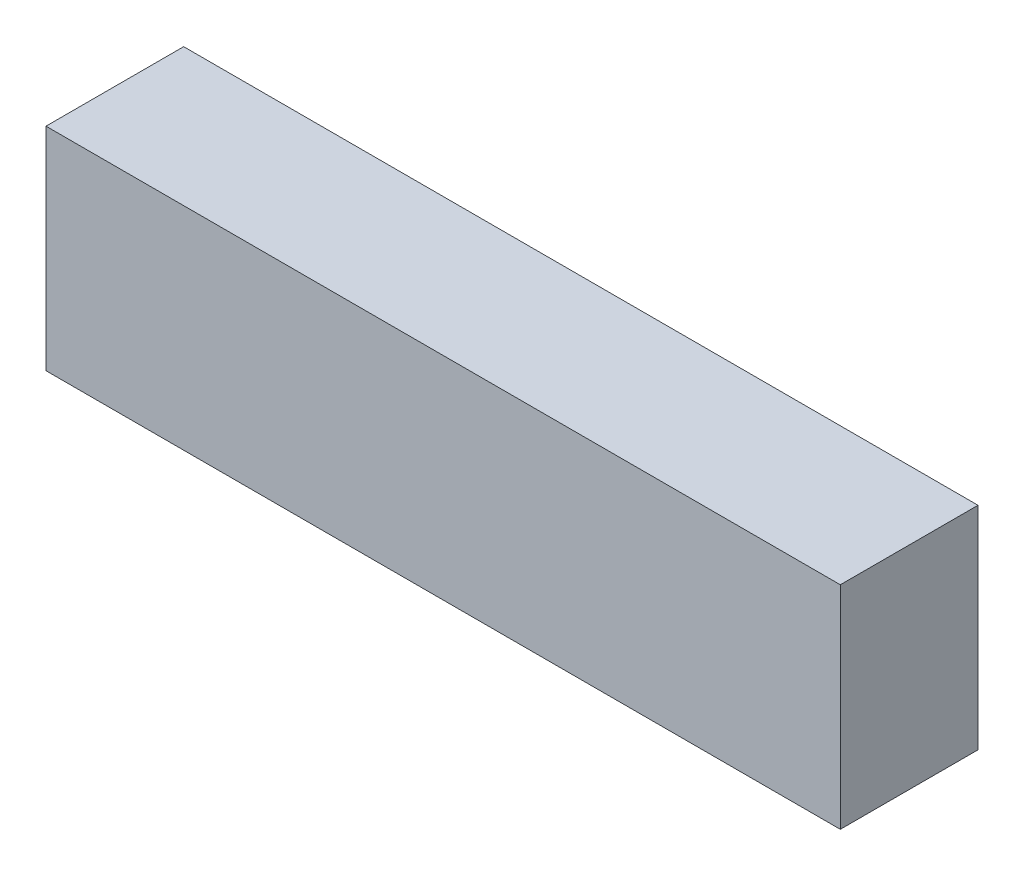
SolidWorks part; units mm, degrees
ref_plane "Спереди" through (0, 0, 0) normal (0, 0, 1) x (1, 0, 0)
ref_plane "Сверху" through (0, 0, 0) normal (0, 1, 0) x (1, 0, 0)
ref_plane "Справа" through (0, 0, 0) normal (1, 0, 0) x (0, 0, -1)
sketch "Эскиз1" plane through (0, 0, 0) normal (0, 0, 1) x (1, 0, 0)
  line L1 (-37.5, -10) -> (37.5, -10)
  line L2 (-37.5, -10) -> (-37.5, 10)
  line L3 (-37.5, 10) -> (37.5, 10)
  line L4 (37.5, -10) -> (37.5, 10)
  line L5 (-37.5, -10) -> (37.5, 10) construction
  line L6 (-37.5, 10) -> (37.5, -10) construction
  point P0 (0, 0)
  dimension "D1" = 75
  dimension "D2" = 20
extrude "Бобышка-Вытянуть1" add sketch "Эскиз1" along normal blind 13
